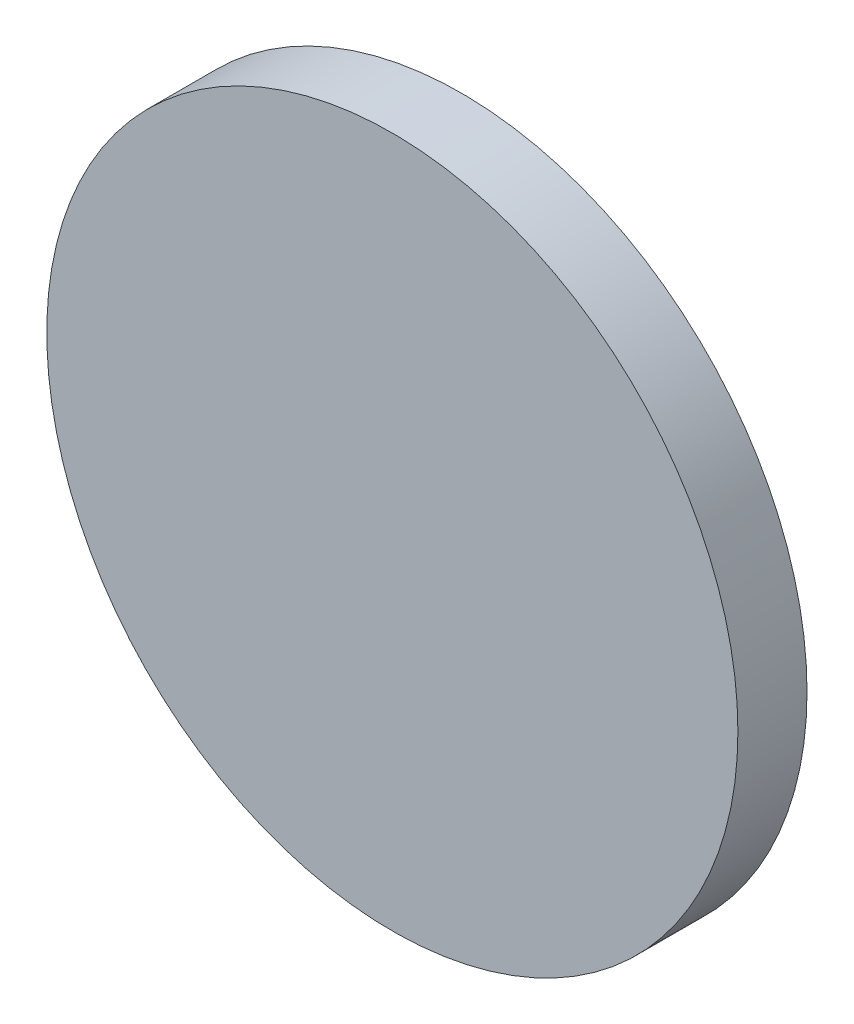
SolidWorks part; units mm, degrees
ref_plane "Front Plane" through (0, 0, 0) normal (0, 0, 1) x (1, 0, 0)
ref_plane "Top Plane" through (0, 0, 0) normal (0, 1, 0) x (1, 0, 0)
ref_plane "Right Plane" through (0, 0, 0) normal (1, 0, 0) x (0, 0, -1)
sketch "Sketch1" plane through (0, 0, 0) normal (0, 0, 1) x (1, 0, 0)
  circle A0 centre (-0.8602, 39.9907) radius 15
  circle A1 centre (-0.8602, 39.9907) radius 4
  dimension "D1" = 30
  dimension "D2" = 8
extrude "Boss-Extrude1" add sketch "Sketch1" along normal blind 3
sketch "Sketch2" plane through (0, 0, 0) normal (0, 0, -1) x (-1, 0, 0)
  circle A0 centre (0.8602, 39.9907) radius 4
  circle A2 centre (0.8602, 39.9907) radius 3.5
  dimension "D1" = 0.5
  dimension "D2" = 8
extrude "Boss-Extrude2" add sketch "Sketch2" along normal blind 5 separate body
sketch "Sketch4" plane through (0, 0, 0) normal (0, 0, 1) x (1, 0, 0)
  circle A1 centre (-0.8602, 39.9907) radius 4
  circle A2 centre (-0.8602, 39.9907) radius 4
  dimension "D1" = 0
extrude "Boss-Extrude4" add sketch "Sketch4" along normal blind 3
